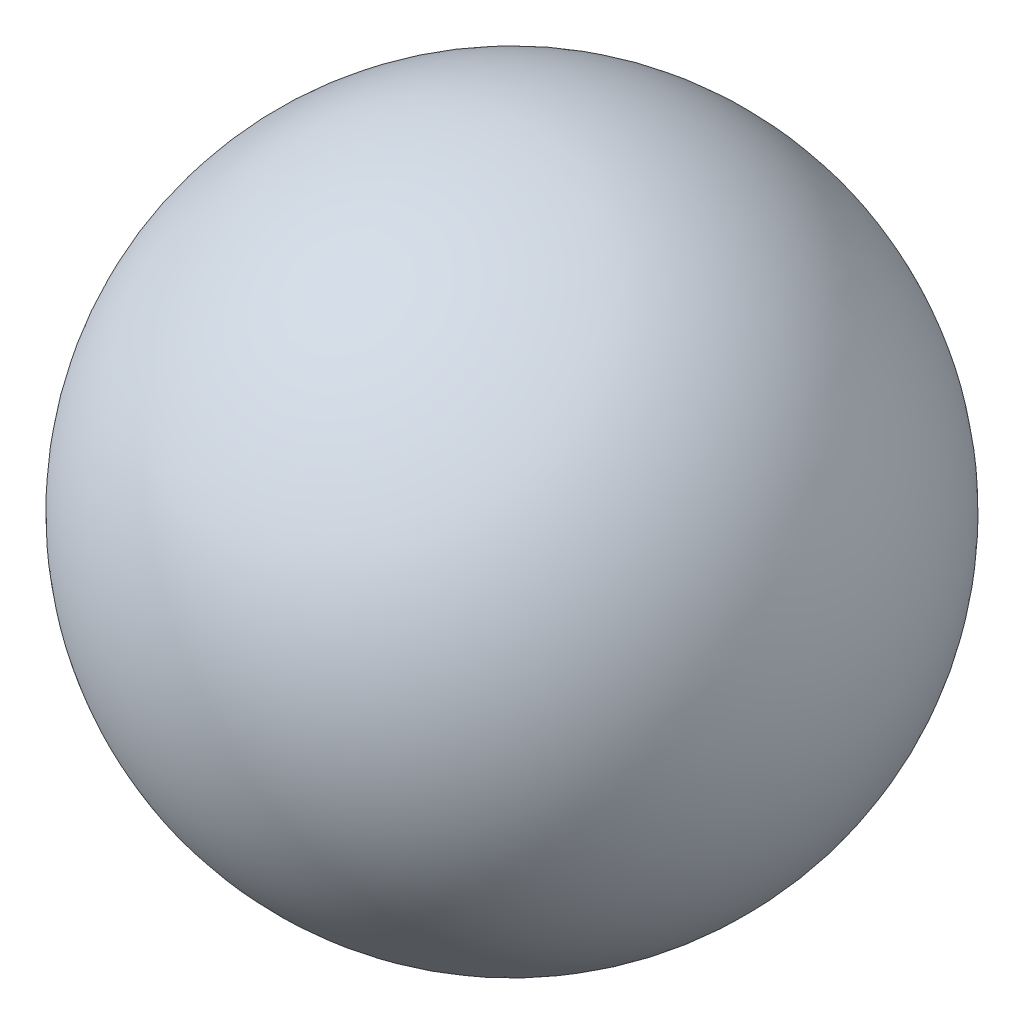
SolidWorks part; units mm, degrees
ref_plane "Front Plane" through (0, 0, 0) normal (0, 0, 1) x (1, 0, 0)
ref_plane "Top Plane" through (0, 0, 0) normal (0, 1, 0) x (1, 0, 0)
ref_plane "Right Plane" through (0, 0, 0) normal (1, 0, 0) x (0, 0, -1)
sketch "Sketch3" plane through (0, 0, 0) normal (0, 1, 0) x (1, 0, 0)
  line L0 (0, 117.2335) -> (0, -117.2335)
  line L1 (0, 0) -> (117.2335, 0)
  arc A0 (0, -117.2335) -> (0, 117.2335) centre (0, 0) ccw
  dimension "D1" = 234.4671
  dimension "D2" = 117.2335
revolve "Revolve1" add sketch "Sketch3" angle 360 about L0
